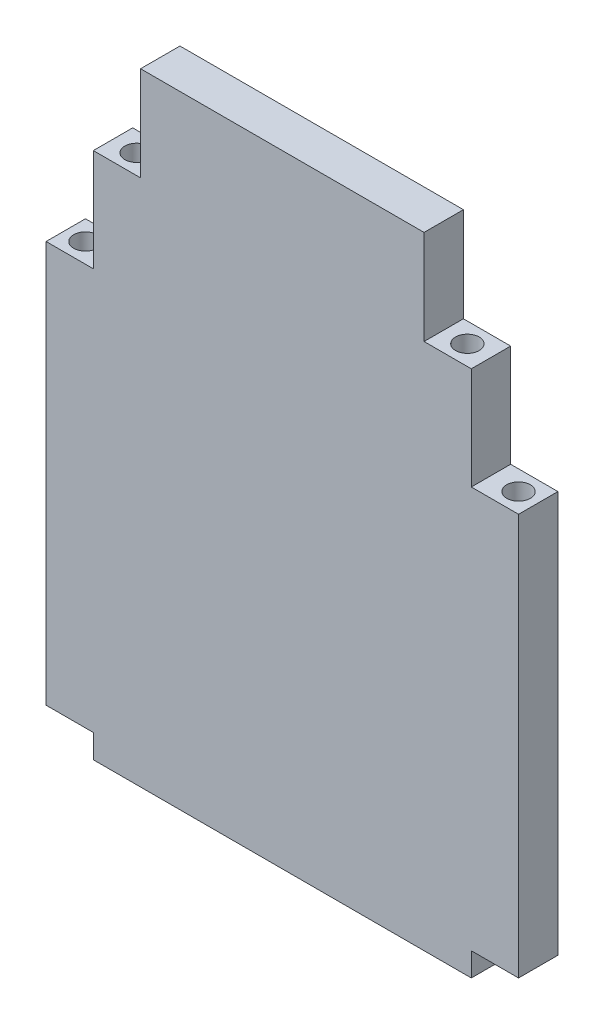
SolidWorks part; units mm, degrees
material "5052-O"
ref_plane "正面" through (0, 0, 0) normal (0, 0, 1) x (1, 0, 0)
ref_plane "平面" through (0, 0, 0) normal (0, 1, 0) x (1, 0, 0)
ref_plane "右側面" through (0, 0, 0) normal (1, 0, 0) x (0, 0, -1)
sketch "ｽｹｯﾁ1" plane through (0, 0, 0) normal (0, 0, 1) x (1, 0, 0)
  line L0 (-30, 0) -> (30, 0) construction
  line L1 (30, -25.5) -> (-30, -25.5) construction
  line L2 (30, -25.5) -> (30, 25.5)
  line L3 (30, 25.5) -> (-30, 25.5) construction
  line L4 (-30, -25.5) -> (-30, 25.5)
  line L5 (30, -25.5) -> (-30, 25.5) construction
  line L6 (30, 25.5) -> (-30, -25.5) construction
  line L7 (-30, 25.5) -> (-24, 25.5)
  line L8 (-24, 25.5) -> (-24, 38.5)
  line L9 (-24, 38.5) -> (-18, 38.5)
  line L10 (24, 38.5) -> (24, 25.5)
  line L11 (24, 25.5) -> (30, 25.5)
  line L12 (-30, -25.5) -> (-24, -25.5)
  line L13 (-24, -25.5) -> (-24, -28.5)
  line L14 (-24, -28.5) -> (24, -28.5)
  line L15 (24, -28.5) -> (24, -25.5)
  line L16 (24, -25.5) -> (30, -25.5)
  line L17 (-18, 38.5) -> (-18, 50.5)
  line L18 (-18, 50.5) -> (18, 50.5)
  line L19 (18, 50.5) -> (18, 38.5)
  line L20 (18, 38.5) -> (24, 38.5)
  point P0 (0, 0)
  dimension "D1" = 60
  dimension "D2" = 51
  dimension "D3" = 13
  dimension "D4" = 6
  dimension "D5" = 3
  dimension "D6" = 12
extrude "ﾎﾞｽ - 押し出し1" add sketch "ｽｹｯﾁ1" along normal blind 5
sketch "ｽｹｯﾁ2" plane through (0, 25.5, 0) normal (0, 1, 0) x (1, 0, 0)
  line L0 (-30, -2.5) -> (30, -2.5) construction
  line L1 (-30, -5) -> (-30, 0) construction
  line L2 (30, -5) -> (30, 0) construction
  line L3 (18, -5) -> (-18, -5) construction
  line L4 (0, 0) -> (0, -5) construction
  circle A0 centre (-27.5, -2.5) radius 1.5
  circle A1 centre (27.5, -2.5) radius 1.5
  dimension "D1" = 2.5
  dimension "D2" = 3
extrude "ｶｯﾄ - 押し出し1" cut sketch "ｽｹｯﾁ2" against normal blind 10
mirror "ﾐﾗｰ1" about plane through (0, 0, 0) normal (0, 1, 0) of "ｶｯﾄ - 押し出し1"
sketch "ｽｹｯﾁ3" plane through (0, 38.5, 0) normal (0, 1, 0) x (1, 0, 0)
  line L0 (-24, 0) -> (-18, -5) construction
  line L2 (0, 0) -> (0, -5) construction
  line L3 (18, -5) -> (-18, -5) construction
  circle A0 centre (-21, -2.5) radius 1.5
  circle A1 centre (-27.5, -2.5) radius 1.5 construction
  circle A2 centre (21, -2.5) radius 1.5
extrude "ｶｯﾄ - 押し出し2" cut sketch "ｽｹｯﾁ3" against normal blind 10
